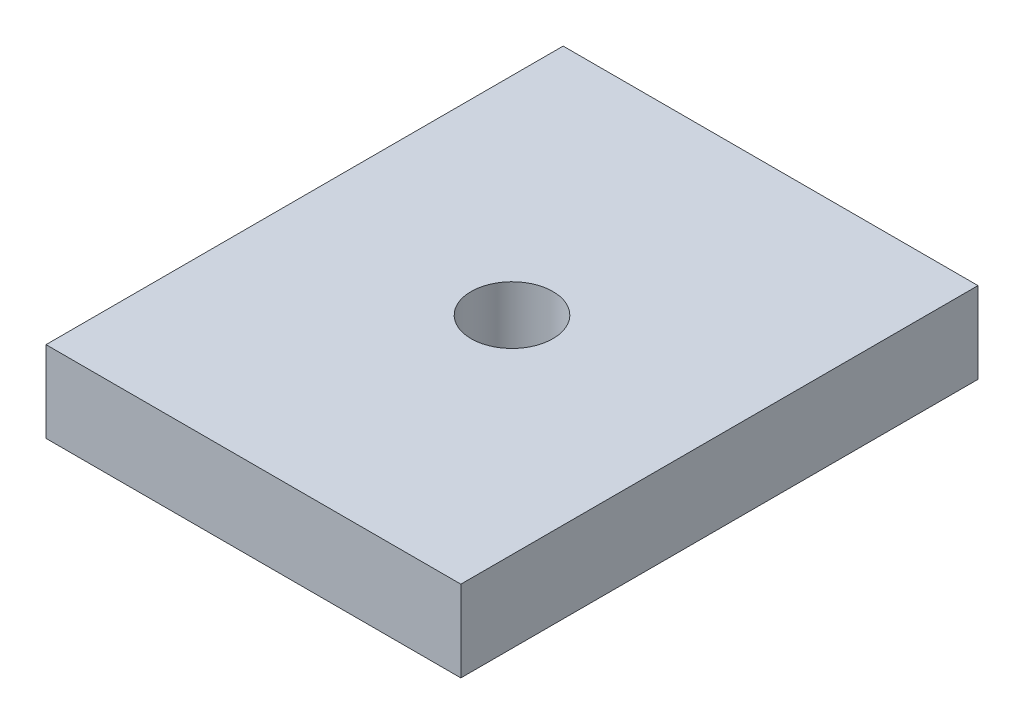
SolidWorks part; units mm, degrees
ref_plane "Front Plane" through (0, 0, 0) normal (0, 0, 1) x (1, 0, 0)
ref_plane "Top Plane" through (0, 0, 0) normal (0, 1, 0) x (1, 0, 0)
ref_plane "Right Plane" through (0, 0, 0) normal (1, 0, 0) x (0, 0, -1)
sketch "Sketch1" plane through (0, 0, 0) normal (0, 1, 0) x (1, 0, 0)
  line L1 (-25.5379, -31.8349) -> (25.5379, -31.8349)
  line L2 (-25.5379, -31.8349) -> (-25.5379, 31.8349)
  line L3 (-25.5379, 31.8349) -> (25.5379, 31.8349)
  line L4 (25.5379, -31.8349) -> (25.5379, 31.8349)
  line L5 (-25.5379, -31.8349) -> (25.5379, 31.8349) construction
  line L6 (-25.5379, 31.8349) -> (25.5379, -31.8349) construction
  point P0 (0, 0)
extrude "Boss-Extrude1" add sketch "Sketch1" along normal blind 10
sketch "Sketch2" plane through (0, 10, 0) normal (0, 1, 0) x (1, 0, 0)
  circle A0 centre (0, 0) radius 5.0366
extrude "Cut-Extrude1" cut sketch "Sketch2" against normal blind 10
